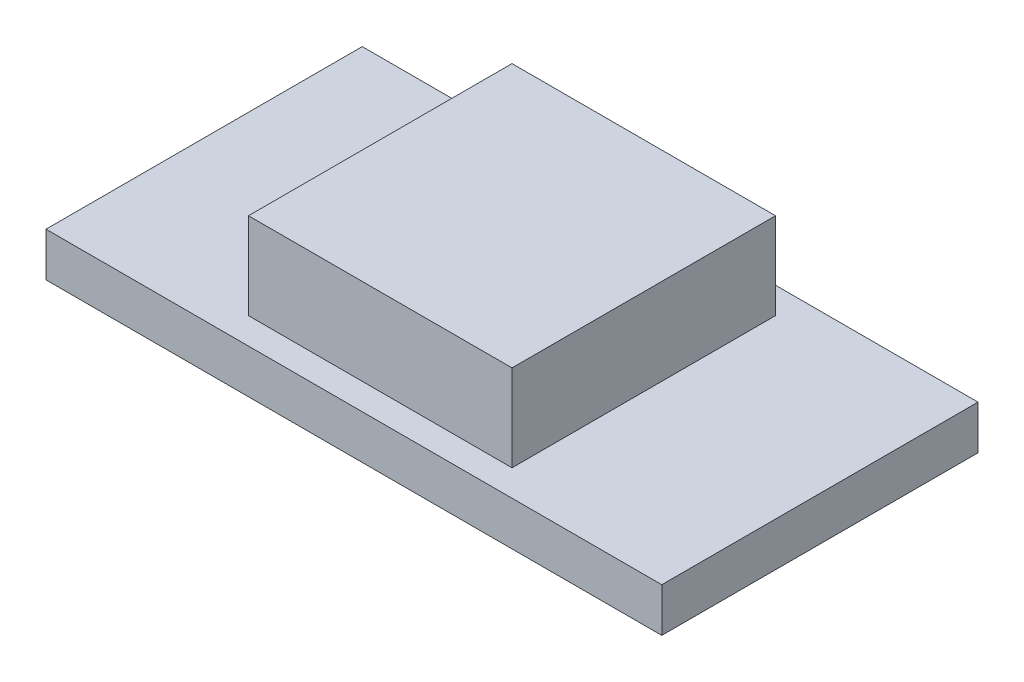
SolidWorks part; units mm, degrees
ref_plane "前基準面" through (0, 0, 0) normal (0, 0, 1) x (1, 0, 0)
ref_plane "上基準面" through (0, 0, 0) normal (0, 1, 0) x (1, 0, 0)
ref_plane "右基準面" through (0, 0, 0) normal (1, 0, 0) x (0, 0, -1)
sketch "草圖1" plane through (0, 0, 0) normal (0, 1, 0) x (1, 0, 0)
  line L1 (-35.05, 18) -> (35.05, 18)
  line L2 (-35.05, 18) -> (-35.05, -18)
  line L3 (-35.05, -18) -> (35.05, -18)
  line L4 (35.05, 18) -> (35.05, -18)
  line L5 (-35.05, 18) -> (35.05, -18) construction
  line L6 (-35.05, -18) -> (35.05, 18) construction
  point P0 (0, 0)
  dimension "D1" = 70.1
  dimension "D2" = 36
extrude "填料-伸長1" add sketch "草圖1" along normal blind 5
sketch "草圖2" plane through (0, 5, 0) normal (0, 1, 0) x (1, 0, 0)
  line L0 (0, -982) -> (0, 49018) construction
  line L1 (35.05, 18) -> (-35.05, 18) construction
  line L2 (-1035.05, 0) -> (48964.95, 0) construction
  line L3 (-35.05, 18) -> (-35.05, -18) construction
  line L5 (-15, 15) -> (15, 15)
  line L6 (-15, 15) -> (-15, -15)
  line L7 (-15, -15) -> (15, -15)
  line L8 (15, 15) -> (15, -15)
  line L9 (-15, 15) -> (15, -15) construction
  line L10 (-15, -15) -> (15, 15) construction
  point P5 (0, 18)
  point P6 (0, 0)
  point P10 (-35.05, 0)
  dimension "D1" = 30
  dimension "D2" = 30
extrude "填料-伸長2" add sketch "草圖2" along normal blind 9.85
